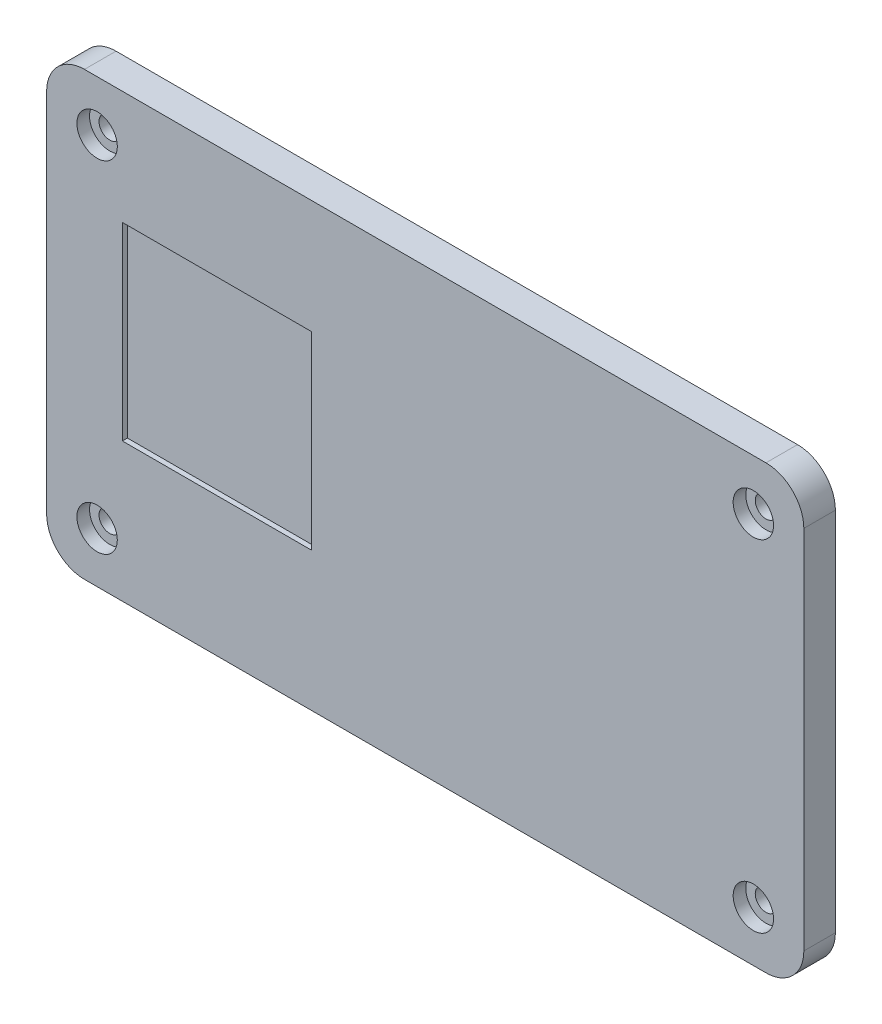
SolidWorks part; units mm, degrees
ref_plane "Front Plane" through (0, 0, 0) normal (0, 0, 1) x (1, 0, 0)
ref_plane "Top Plane" through (0, 0, 0) normal (0, 1, 0) x (1, 0, 0)
ref_plane "Right Plane" through (0, 0, 0) normal (1, 0, 0) x (0, 0, -1)
sketch "Sketch1" plane through (0, 0, 0) normal (0, 0, 1) x (1, 0, 0)
  line L1 (-60, 35) -> (60, 35)
  line L2 (-60, 35) -> (-60, -35)
  line L3 (-60, -35) -> (60, -35)
  line L4 (60, 35) -> (60, -35)
  point P4 (0, 35)
  point P6 (60, 0)
  dimension "D1" = 120
  dimension "D2" = 70
extrude "Boss-Extrude1" add sketch "Sketch1" along normal blind 5
fillet "Fillet1" radius 6 4 edges at (60, -35, 2.5) (-60, -35, 2.5) (-60, 35, 2.5) (60, 35, 2.5)
sketch "Sketch2" plane through (0, 0, 0) normal (0, 0, -1) x (-1, 0, 0)
  line L1 (-53.75, 31.75) -> (53.75, 31.75)
  line L2 (-56.75, 28.75) -> (-56.75, -28.75)
  line L3 (-53.75, -31.75) -> (53.75, -31.75)
  line L4 (56.75, 28.75) -> (56.75, -28.75)
  line L5 (-51.75, 29.75) -> (51.75, 29.75)
  line L6 (-54.75, 26.75) -> (-54.75, -26.75)
  line L7 (-51.75, -29.75) -> (51.75, -29.75)
  line L8 (54.75, 26.75) -> (54.75, -26.75)
  arc A0 (51.75, 29.75) -> (54.75, 26.75) centre (51.75, 26.75) cw
  arc A1 (53.75, 31.75) -> (56.75, 28.75) centre (53.75, 28.75) cw
  arc A2 (53.75, -31.75) -> (56.75, -28.75) centre (53.75, -28.75) ccw
  arc A3 (51.75, -29.75) -> (54.75, -26.75) centre (51.75, -26.75) ccw
  arc A4 (-54.75, -26.75) -> (-51.75, -29.75) centre (-51.75, -26.75) ccw
  arc A5 (-56.75, -28.75) -> (-53.75, -31.75) centre (-53.75, -28.75) ccw
  arc A6 (-53.75, 31.75) -> (-56.75, 28.75) centre (-53.75, 28.75) ccw
  arc A7 (-51.75, 29.75) -> (-54.75, 26.75) centre (-51.75, 26.75) ccw
  point P4 (0, 31.75)
  point P6 (-56.75, 0)
  point P11 (0, 29.75)
  point P12 (-54.75, 0)
  point P15 (54.75, 29.75)
  point P18 (56.75, 31.75)
  point P21 (56.75, -31.75)
  point P24 (54.75, -29.75)
  point P31 (-56.75, 31.75)
  point P34 (-54.75, 29.75)
  dimension "D5" = 3
  dimension "D1" = 113.5
  dimension "D2" = 63.5
  dimension "D3" = 109.5
  dimension "D4" = 59.5
extrude "Boss-Extrude2" add sketch "Sketch2" along normal blind 3
sketch "Sketch3" plane through (0, 0, -3) normal (0, 0, -1) x (-1, 0, 0)
  line L0 (4.4, 0) -> (-4.4, 0) construction
  line L1 (0, 4.4) -> (0, -4.4) construction
  circle A0 centre (-52, 27) radius 5.5
  circle A1 centre (-52, -27) radius 5.5
  circle A2 centre (52, -27) radius 5.5
  circle A3 centre (52, 27) radius 5.5
  point P13 (0, 0)
  dimension "D1" = 11
  dimension "D2" = 52
  dimension "D3" = 27
extrude "Cut-Extrude1" cut sketch "Sketch3" against normal blind 2
sketch "Sketch4" plane through (0, 0, 5) normal (0, 0, 1) x (1, 0, 0)
  line L0 (4.4, 0) -> (-4.4, 0) construction
  line L1 (0, -4.4) -> (0, 4.4) construction
  circle A0 centre (52, 27) radius 3.2
  circle A1 centre (52, -27) radius 3.2
  circle A2 centre (-52, -27) radius 3.2
  circle A3 centre (-52, 27) radius 3.2
  dimension "D1" = 6.4
  dimension "D2" = 52
  dimension "D3" = 27
extrude "Cut-Extrude2" cut sketch "Sketch4" against normal blind 2
sketch "Sketch5" plane through (0, 0, 3) normal (0, 0, 1) x (1, 0, 0)
  line L0 (4.4, 0) -> (-4.4, 0) construction
  line L1 (0, -4.4) -> (0, 4.4) construction
  circle A0 centre (52, 27) radius 1.7
  circle A1 centre (52, 27) radius 3.2 construction
  circle A2 centre (52, -27) radius 1.7
  circle A3 centre (-52, -27) radius 1.7
  circle A4 centre (-52, 27) radius 1.7
  dimension "D1" = 3.4
extrude "Cut-Extrude3" cut sketch "Sketch5" against normal through all
sketch "Sketch6" plane through (0, 0, 0) normal (0, 0, -1) x (-1, 0, 0)
  line L1 (-54, 34.1) -> (54, 34.1)
  line L2 (-59.1, 29) -> (-59.1, -29)
  line L3 (-54, -34.1) -> (54, -34.1)
  line L4 (59.1, 29) -> (59.1, -29)
  line L5 (-54, 32.9) -> (54, 32.9)
  line L6 (-57.9, 29) -> (-57.9, -29)
  line L7 (-54, -32.9) -> (54, -32.9)
  line L8 (57.9, 29) -> (57.9, -29)
  arc A0 (54, -34.1) -> (59.1, -29) centre (54, -29) ccw
  arc A1 (-59.1, -29) -> (-54, -34.1) centre (-54, -29) ccw
  arc A2 (-54, 34.1) -> (-59.1, 29) centre (-54, 29) ccw
  arc A3 (54, 34.1) -> (59.1, 29) centre (54, 29) cw
  arc A4 (54, -32.9) -> (57.9, -29) centre (54, -29) ccw
  arc A5 (-57.9, -29) -> (-54, -32.9) centre (-54, -29) ccw
  arc A6 (-54, 32.9) -> (-57.9, 29) centre (-54, 29) ccw
  arc A7 (54, 32.9) -> (57.9, 29) centre (54, 29) cw
  point P4 (0, 34.1)
  point P6 (-59.1, 0)
  point P9 (59.1, -34.1)
  point P14 (-59.1, 34.1)
  point P17 (59.1, 34.1)
  point P22 (0, 32.9)
  point P23 (-57.9, 0)
  point P28 (-57.9, -32.9)
  point P31 (-57.9, 32.9)
  point P34 (57.9, 32.9)
  dimension "D3" = 5.1
  dimension "D6" = 3.9
  dimension "D1" = 118.2
  dimension "D2" = 68.2
  dimension "D4" = 115.8
  dimension "D5" = 65.8
extrude "Cut-Extrude4" cut sketch "Sketch6" against normal blind 1
sketch "Sketch7" plane through (0, 0, 5) normal (0, 0, 1) x (1, 0, 0)
  line L1 (-48, 17) -> (-18, 17)
  line L2 (-48, 17) -> (-48, -13)
  line L3 (-48, -13) -> (-18, -13)
  line L4 (-18, 17) -> (-18, -13)
  point P4 (-33, 17)
  point P5 (-18, 2)
  dimension "D1" = 30
  dimension "D2" = 30
  dimension "D3" = 33
  dimension "D4" = 2
extrude "Cut-Extrude5" cut sketch "Sketch7" against normal blind 0.8
